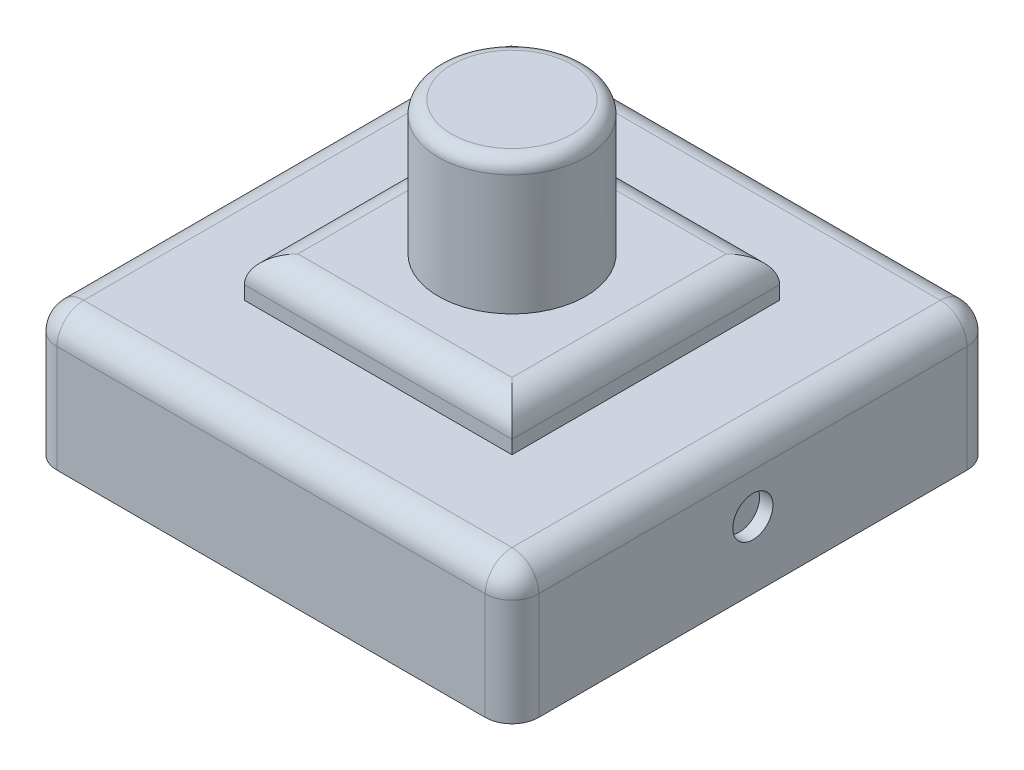
SolidWorks part; units mm, degrees
ref_plane "前视基准面" through (0, 0, 0) normal (0, 0, 1) x (1, 0, 0)
ref_plane "上视基准面" through (0, 0, 0) normal (0, 1, 0) x (1, 0, 0)
ref_plane "右视基准面" through (0, 0, 0) normal (1, 0, 0) x (0, 0, -1)
sketch "草图1" plane through (0, 0, 0) normal (0, 1, 0) x (1, 0, 0)
  line L1 (-18, -18) -> (18, -18)
  line L2 (-18, -18) -> (-18, 18)
  line L3 (-18, 18) -> (18, 18)
  line L4 (18, -18) -> (18, 18)
  line L5 (0, 18) -> (0, -18) construction
  line L6 (-18, 0) -> (18, 0) construction
  point P0 (0, 0)
  dimension "D1" = 36
  dimension "D2" = 36
extrude "凸台-拉伸1" add sketch "草图1" against normal blind 10
sketch "草图2" plane through (0, 0, 0) normal (0, 1, 0) x (1, 0, 0)
  line L1 (-10, -10) -> (10, -10)
  line L2 (-10, -10) -> (-10, 10)
  line L3 (-10, 10) -> (10, 10)
  line L4 (10, -10) -> (10, 10)
  line L5 (0, 10) -> (0, -10) construction
  line L6 (-10, 0) -> (10, 0) construction
  point P0 (0, 0)
  dimension "D1" = 20
  dimension "D2" = 20
extrude "凸台-拉伸2" add sketch "草图2" along normal blind 3
sketch "草图3" plane through (0, 3, 0) normal (0, 1, 0) x (1, 0, 0)
  circle A0 centre (0, 0) radius 5.5
extrude "凸台-拉伸4" add sketch "草图3" along normal blind 10
sketch "草图4" plane through (-18, 0, 0) normal (-1, 0, 0) x (0, 0, 1)
  line L1 (-18, -10) -> (18, -10)
  line L2 (-18, -10) -> (-18, 0)
  line L3 (-18, 0) -> (18, 0)
  line L4 (18, -10) -> (18, 0)
  line L5 (-18, -10) -> (18, 0) construction
  line L6 (-18, 0) -> (18, -10) construction
  circle A0 centre (0, -5) radius 1.5
  point P4 (0, -5)
extrude "切除-拉伸1" cut sketch "草图4" against normal blind 1 contours A0
sketch "草图5" plane through (18, 0, 0) normal (1, 0, 0) x (0, 0, -1)
  line L1 (-18, -10) -> (18, -10)
  line L2 (-18, -10) -> (-18, 0)
  line L3 (-18, 0) -> (18, 0)
  line L4 (18, -10) -> (18, 0)
  line L5 (-18, -10) -> (18, 0) construction
  line L6 (-18, 0) -> (18, -10) construction
  circle A0 centre (0, -5) radius 1.5
  point P4 (0, -5)
extrude "切除-拉伸2" cut sketch "草图5" against normal blind 1 contours A0
fillet "圆角1" radius 2 12 edges at (-10, 3, 0) (0, 3, -10) (10, 3, 0) (0, 3, 10) (0, 0, 18) (-18, 0, 0) (0, 0, -18) (18, 0, 0) (18, -5, -18) (18, -5, 18) (-18, -5, 18) (-18, -5, -18)
fillet "圆角2" radius 1 1 edges at (0, 13, 5.5)
